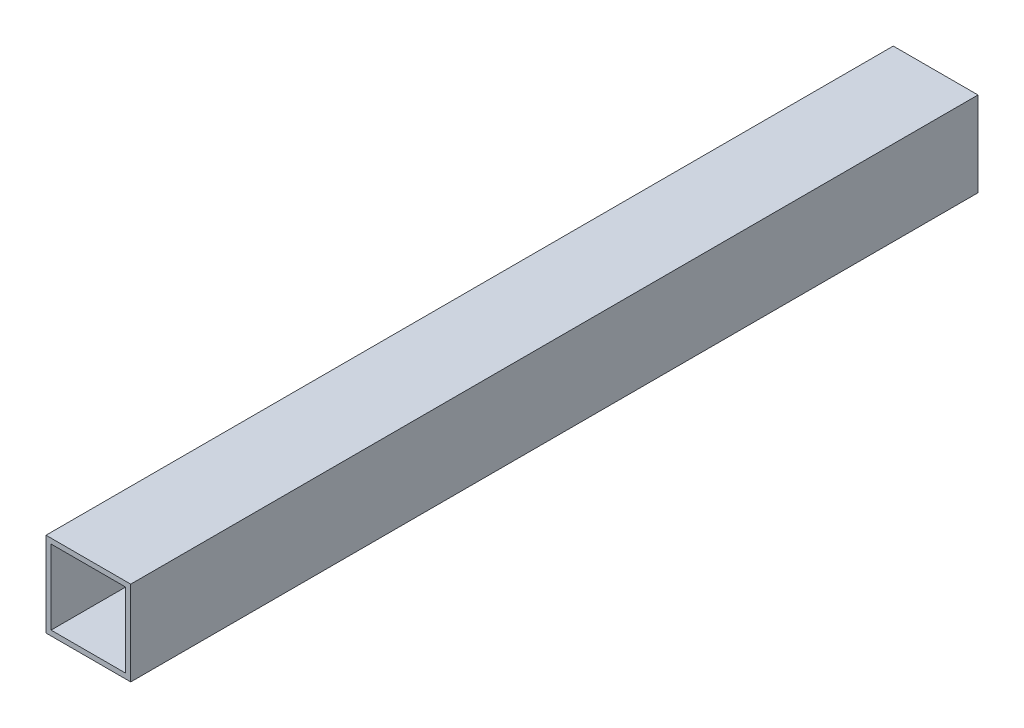
SolidWorks part; units mm, degrees
ref_plane "Front" through (0, 0, 0) normal (0, 0, 1) x (1, 0, 0)
ref_plane "Top" through (0, 0, 0) normal (0, 1, 0) x (1, 0, 0)
ref_plane "Right" through (0, 0, 0) normal (1, 0, 0) x (0, 0, -1)
sketch "Эскиз1" plane through (0, 0, 0) normal (0, 0, 1) x (1, 0, 0)
  line L1 (-12.5, -12.5) -> (12.5, -12.5)
  line L2 (-12.5, -12.5) -> (-12.5, 12.5)
  line L3 (-12.5, 12.5) -> (12.5, 12.5)
  line L4 (12.5, -12.5) -> (12.5, 12.5)
  line L5 (-12.5, -12.5) -> (12.5, 12.5) construction
  line L6 (-12.5, 12.5) -> (12.5, -12.5) construction
  point P0 (0, 0)
  dimension "D1" = 25
  dimension "D2" = 25
extrude "Вытянуть-Тонкостенный1" add sketch "Эскиз1" along normal blind 250 thin thin type one direction reverse wall 1.5
